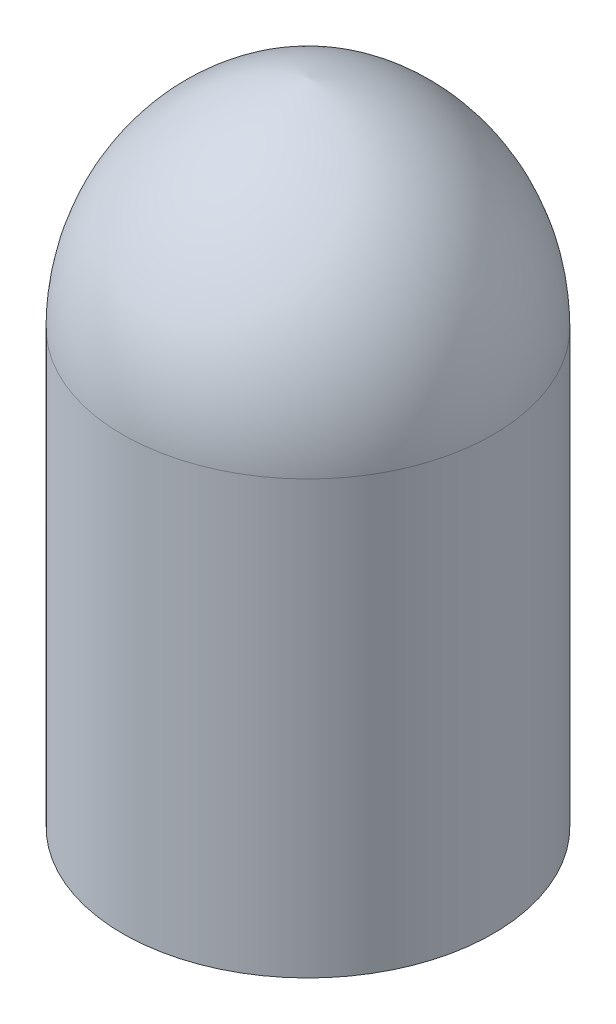
SolidWorks part; units mm, degrees
ref_plane "Front Plane" through (0, 0, 0) normal (0, 0, 1) x (1, 0, 0)
ref_plane "Top Plane" through (0, 0, 0) normal (0, 1, 0) x (1, 0, 0)
ref_plane "Right Plane" through (0, 0, 0) normal (1, 0, 0) x (0, 0, -1)
sketch "Sketch1" plane through (0, 0, 0) normal (0, 0, 1) x (1, 0, 0)
  line L0 (0, 0) -> (60, 0)
  line L1 (60, 0) -> (60, 140)
  line L2 (0, 210) -> (0, 0)
  arc A0 (60, 140) -> (0, 210) centre (-10.8333, 140) ccw
  point P6 (0, 0)
  point P7 (0, 0)
  point P8 (0, 0)
  point P9 (0, 0)
  point P10 (0, 0)
  point P11 (61.173, 136.9355)
  point P12 (0, 0)
  point P13 (0, 0)
  point P14 (0, 0)
  point P15 (64.3483, 134.7128)
  point P16 (0, 0)
  point P17 (0, 0)
  dimension "D2" = 60
  dimension "D1" = 210
  dimension "D4" = 140
revolve "Revolve2" add sketch "Sketch1" angle 360 about L2
shell "Shell3" thickness 2
